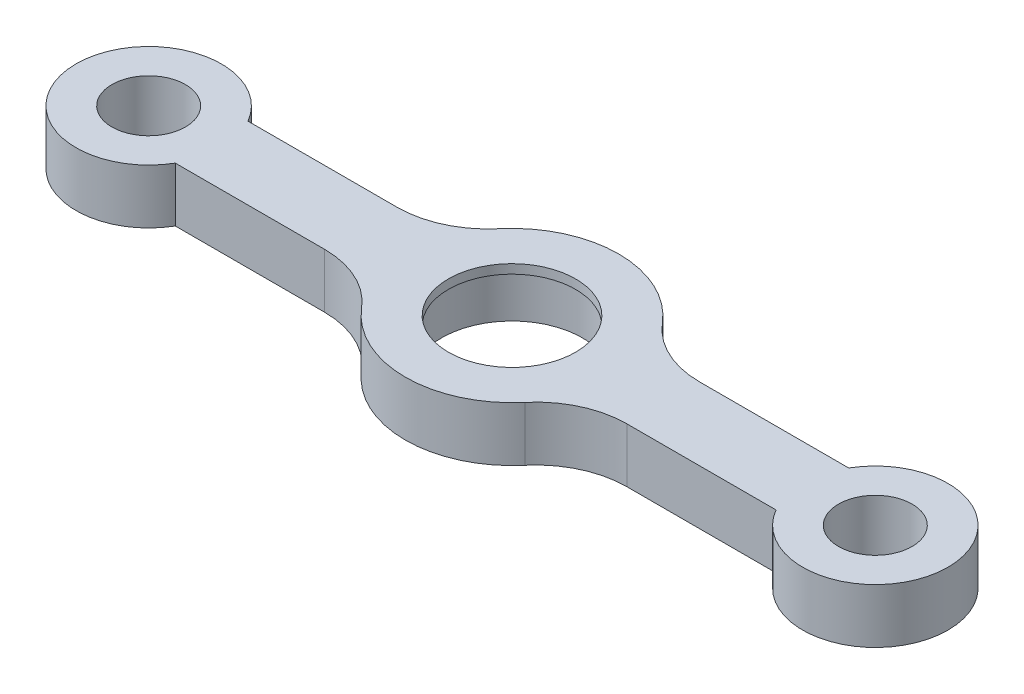
SolidWorks part; units mm, degrees
material "ABS"
ref_plane "Plano frontal" through (0, 0, 0) normal (0, 0, 1) x (1, 0, 0)
ref_plane "Plano superior" through (0, 0, 0) normal (0, 1, 0) x (1, 0, 0)
ref_plane "Plano direito" through (0, 0, 0) normal (1, 0, 0) x (0, 0, -1)
sketch "Esboço1" plane through (0, 0, 0) normal (0, 1, 0) x (1, 0, 0)
  line L0 (-40, 0) -> (40, 0) construction
  line L1 (-33.0718, 4) -> (-16.6452, 4)
  line L2 (-33.0718, -4) -> (-16.6452, -4)
  line L3 (16.6452, 4) -> (33.0718, 4)
  line L4 (16.6452, -4) -> (33.0718, -4)
  arc A0 (-33.0718, 4) -> (-33.0718, -4) centre (-40, 0) ccw
  arc A1 (33.0718, -4) -> (33.0718, 4) centre (40, 0) ccw
  circle A2 centre (40, 0) radius 4.05
  circle A3 centre (-40, 0) radius 4.05
  arc A4 (-8.9922, -7.5632) -> (8.9922, -7.5632) centre (0, 0) ccw
  arc A5 (8.9922, 7.5632) -> (-8.9922, 7.5632) centre (0, 0) ccw
  circle A6 centre (0, 0) radius 7.75
  arc A7 (-8.9922, -7.5632) -> (-16.6452, -4) centre (-16.6452, -14) ccw
  arc A8 (16.6452, -4) -> (8.9922, -7.5632) centre (16.6452, -14) ccw
  arc A9 (16.6452, 4) -> (8.9922, 7.5632) centre (16.6452, 14) cw
  arc A10 (-8.9922, 7.5632) -> (-16.6452, 4) centre (-16.6452, 14) cw
  point P4 (0, 0)
  point P22 (11.0482, 4)
  dimension "D2" = 8.1
  dimension "D3" = 16
  dimension "D5" = 4
  dimension "D6" = 15.5
  dimension "D7" = 10
  dimension "D1" = 80
  dimension "D4" = 8
extrude "Ressalto-extrusão1" add sketch "Esboço1" along normal blind 6
sketch "Esboço2" plane through (0, 6, 0) normal (0, 1, 0) x (1, 0, 0)
  circle A0 centre (0, 0) radius 7
  circle A1 centre (0, 0) radius 7.75
  dimension "D1" = 14
extrude "Ressalto-extrusão2" add sketch "Esboço2" against normal blind 1
